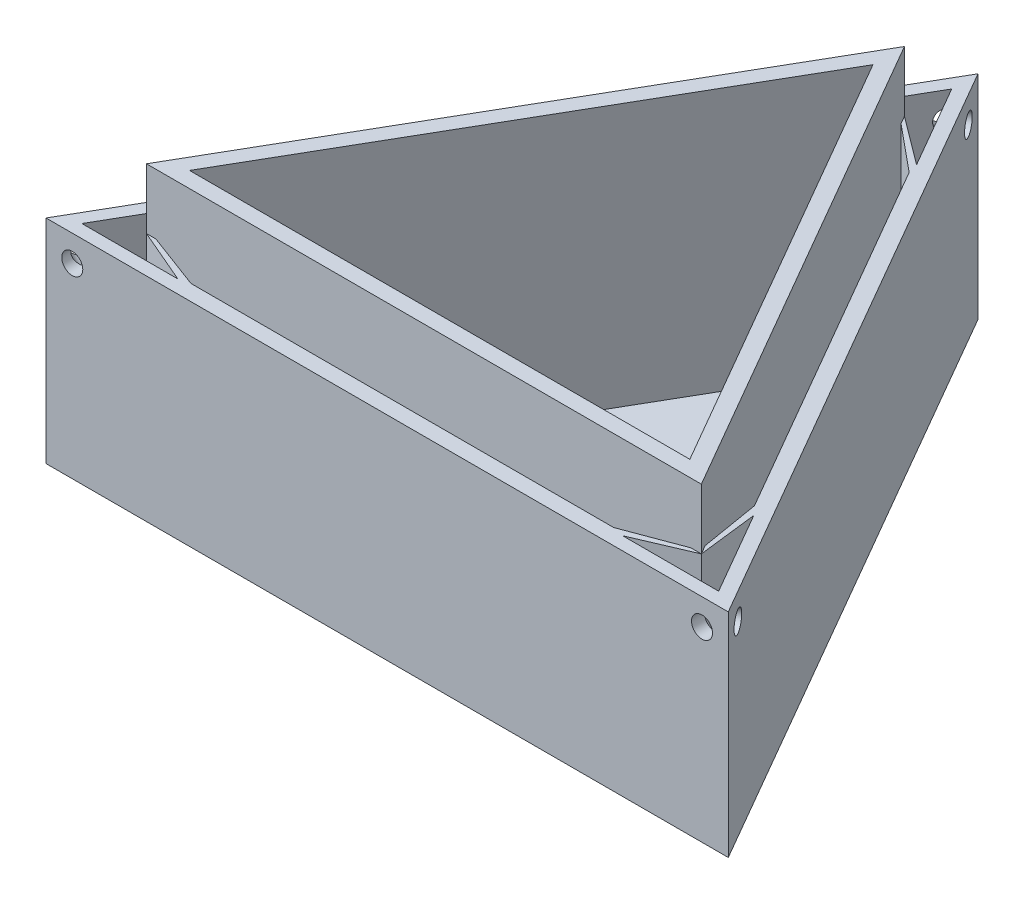
SolidWorks part; units mm, degrees
ref_plane "Front Plane" through (0, 0, 0) normal (0, 0, 1) x (1, 0, 0)
ref_plane "Top Plane" through (0, 0, 0) normal (0, 1, 0) x (1, 0, 0)
ref_plane "Right Plane" through (0, 0, 0) normal (1, 0, 0) x (0, 0, -1)
ref_plane "Plane1" through (0, -0.5, 0) normal (0, -1, 0) x (1, 0, 0)
sketch "Sketch1" plane through (0, -0.5, 0) normal (0, -1, 0) x (1, 0, 0)
  line L0 (64.9519, 37.5) -> (-64.9519, 37.5)
  line L1 (-64.9519, 37.5) -> (0, -75)
  line L2 (0, -75) -> (64.9519, 37.5)
extrude "Boss-Extrude1" add sketch "Sketch1" against normal blind 40.5
sketch "Sketch4" plane through (0, 40, 0) normal (0, 1, 0) x (-1, 0, 0)
  line L0 (0, -61) -> (-52.8275, 30.5)
  line L1 (-52.8275, 30.5) -> (52.8275, 30.5)
  line L2 (52.8275, 30.5) -> (0, -61)
extrude "Boss-Extrude2" add sketch "Sketch4" along normal blind 11.5
sketch "Sketch2" plane through (0, 40, 0) normal (0, 1, 0) x (-1, 0, 0)
  line L0 (-0.8996, -59.4418) -> (-51.8275, 28.7679)
  line L1 (-52.8275, 30.5) -> (0, -61) construction
  line L2 (0, -75) -> (-64.9519, 37.5) construction
  line L3 (-49.9476, 17.5119) -> (-9.7078, -52.1857)
  spline S0 degree 1 poles (-49.9476, 17.5119) (-51.8275, 28.7679) knots 0 0 1 1
  spline S2 degree 1 poles (-0.8996, -59.4418) (-9.7078, -52.1857) knots 0 0 1 1
  dimension "D1" = 3
extrude "Cut-Extrude1" cut sketch "Sketch2" against normal blind 38.5
sketch "Sketch3" plane through (0, 40, 0) normal (0, 1, 0) x (-1, 0, 0)
  line L0 (-50.8275, 30.5) -> (51.0283, 30.5)
  line L1 (52.8275, 30.5) -> (-52.8275, 30.5) construction
  line L3 (40.3402, 34.5) -> (-40.1395, 34.5)
  line L4 (-64.9519, 37.5) -> (64.9519, 37.5) construction
  spline S1 degree 1 poles (-50.8275, 30.5) (-40.1395, 34.5) knots 0 0 1 1
  spline S2 degree 1 poles (40.3402, 34.5) (51.0283, 30.5) knots 0 0 1 1
  dimension "D1" = 3
extrude "Cut-Extrude2" cut sketch "Sketch3" against normal blind 38.5
sketch "Sketch5" plane through (0, 40, 0) normal (0, 1, 0) x (-1, 0, 0)
  line L0 (50.048, 17.6857) -> (51.8275, 28.7679)
  line L1 (51.8275, 28.7679) -> (1, -59.2679)
  line L2 (1, -59.2679) -> (9.7078, -52.1857)
  line L3 (9.7078, -52.1857) -> (50.048, 17.6857)
  line L4 (64.9519, 37.5) -> (0, -75) construction
  line L5 (0, -61) -> (52.8275, 30.5) construction
  dimension "D1" = 3
extrude "Cut-Extrude3" cut sketch "Sketch5" against normal blind 38.5
sketch "Sketch6" plane through (0, 40, 0) normal (0, 1, 0) x (-1, 0, 0)
  spline S0 degree 1 poles (-42.3402, 35) (-60.6218, 35) knots 0 0 1 1
  spline S1 degree 1 poles (-51.481, 19.1677) (-60.6218, 35) knots 0 0 1 1
  spline S2 degree 1 poles (-52.8275, 30.5) (-51.481, 19.1677) knots 0 0 1 1
  spline S3 degree 1 poles (-42.3402, 35) (-52.8275, 30.5) knots 0 0 1 1
extrude "Cut-Extrude4" cut sketch "Sketch6" against normal blind 38.5
sketch "Sketch7" plane through (0, 40, 0) normal (0, 1, 0) x (-1, 0, 0)
  spline S0 degree 1 poles (60.6218, 35) (51.481, 19.1677) knots 0 0 1 1
  spline S1 degree 1 poles (60.6218, 35) (42.3402, 35) knots 0 0 1 1
  spline S2 degree 1 poles (52.8275, 30.5) (42.3402, 35) knots 0 0 1 1
  spline S3 degree 1 poles (51.481, 19.1677) (52.8275, 30.5) knots 0 0 1 1
extrude "Cut-Extrude5" cut sketch "Sketch7" against normal blind 38.5
sketch "Sketch8" plane through (0, 40, 0) normal (0, 1, 0) x (-1, 0, 0)
  spline S0 degree 1 poles (0, -70) (-9.1408, -54.1677) knots 0 0 1 1
  spline S1 degree 1 poles (9.1408, -54.1677) (0, -70) knots 0 0 1 1
  spline S2 degree 1 poles (0, -61) (9.1408, -54.1677) knots 0 0 1 1
  spline S3 degree 1 poles (-9.1408, -54.1677) (0, -61) knots 0 0 1 1
extrude "Cut-Extrude6" cut sketch "Sketch8" against normal blind 38.5
sketch "Sketch9" plane through (0, 51.5, 0) normal (0, 1, 0) x (-1, 0, 0)
  line L0 (47.6314, 27.5) -> (-47.6314, 27.5)
  line L1 (-47.6314, 27.5) -> (0, -55)
  line L2 (0, -55) -> (47.6314, 27.5)
  line L3 (52.8275, 30.5) -> (-52.8275, 30.5) construction
  line L4 (0, -61) -> (52.8275, 30.5) construction
  line L6 (-52.8275, 30.5) -> (0, -61) construction
  dimension "D1" = 3
  dimension "D2" = 3
  dimension "D3" = 3
extrude "Cut-Extrude7" cut sketch "Sketch9" against normal blind 50
hole_wizard "Ø18.0 (18) Diameter Hole1" positions "Sketch11" profile "Sketch10" hole size "Ø18.0" standard "ANSI Metric"
sketch "Sketch11" plane through (0, -0.5, 0) normal (0, -1, 0) x (-1, 0, 0)
  point P0 (0, 0)
sketch "Sketch10" plane through (0, -0.5, 0) normal (1, 0, 0) x (0, 0, -1)
  line L0 (0, 0) -> (0, 52)
  line L1 (0, 52) -> (9, 52)
  line L2 (9, 52) -> (9, 0)
  line L5 (9, 0) -> (0, 0)
  line L11 (0, -6.35) -> (0, 107.95) construction
  dimension "Thru Hole Dia." = 18
  dimension "Thru Hole Depth" = 52
hole_wizard "Ø2.45 (2.45) Diameter Hole1" positions "Sketch13" profile "Sketch12" hole size "Ø2.45" standard "ANSI Metric"
sketch "Sketch13" plane through (0, 1.5, 0) normal (0, 1, 0) x (1, 0, 0)
  point P0 (13.95, 13.95)
  point P1 (-13.95, -13.95)
  point P2 (13.95, -13.95)
  point P3 (-13.95, 13.95)
sketch "Sketch12" plane through (13.95, 1.5, -13.95) normal (1, 0, 0) x (0, 0, 1)
  line L0 (0, 0) -> (0, 2)
  line L1 (0, 2) -> (1.225, 2)
  line L2 (1.225, 2) -> (1.225, 0)
  line L5 (1.225, 0) -> (0, 0)
  line L11 (0, -6.35) -> (0, 107.95) construction
  dimension "Thru Hole Dia." = 2.45
  dimension "Thru Hole Depth" = 2
hole_wizard "Ø4.0 (4) Diameter Hole1" positions "Sketch15" profile "Sketch14" hole size "Ø4.0" standard "ANSI Metric"
sketch "Sketch15" plane through (0, 0, 37.5) normal (0, 0, 1) x (1, 0, 0)
  point P0 (59.9519, 35)
  point P1 (-59.9519, 35)
sketch "Sketch14" plane through (59.9519, 35, 37.5) normal (1, 0, 0) x (0, -1, 0)
  line L0 (0, 0) -> (0, 3)
  line L1 (0, 3) -> (2, 3)
  line L2 (2, 3) -> (2, 0)
  line L5 (2, 0) -> (0, 0)
  line L10 (0, 3) -> (-2, 3) construction
  line L11 (0, -6.35) -> (0, 107.95) construction
  dimension "Hole Dia." = 4
  dimension "Hole Depth" = 3
  dimension "Drill Angle" = 180
hole_wizard "Ø4.0 (4) Diameter Hole2" positions "Sketch17" profile "Sketch16" hole size "Ø4.0" standard "ANSI Metric"
sketch "Sketch17" plane through (-32.476, 0, -18.75) normal (-0.866, 0, -0.5) x (-0.5, 0, 0.866)
  point P0 (-59.9519, 35)
  point P1 (59.9519, 35)
sketch "Sketch16" plane through (-2.5, 35, -70.6699) normal (0, 1, 0) x (-0.5, 0, 0.866)
  line L0 (0, 0) -> (0, 3)
  line L1 (0, 3) -> (2, 3)
  line L2 (2, 3) -> (2, 0)
  line L5 (2, 0) -> (0, 0)
  line L10 (0, 3) -> (-2, 3) construction
  line L11 (0, -6.35) -> (0, 107.95) construction
  dimension "Hole Dia." = 4
  dimension "Hole Depth" = 3
  dimension "Drill Angle" = 180
hole_wizard "Ø4.0 (4) Diameter Hole3" positions "Sketch19" profile "Sketch18" hole size "Ø4.0" standard "ANSI Metric"
sketch "Sketch19" plane through (32.476, 0, -18.75) normal (0.866, 0, -0.5) x (-0.5, 0, -0.866)
  point P0 (59.9519, 35)
  point P1 (-59.9519, 35)
sketch "Sketch18" plane through (2.5, 35, -70.6699) normal (0, 1, 0) x (-0.5, 0, -0.866)
  line L0 (0, 0) -> (0, 3)
  line L1 (0, 3) -> (2, 3)
  line L2 (2, 3) -> (2, 0)
  line L5 (2, 0) -> (0, 0)
  line L10 (0, 3) -> (-2, 3) construction
  line L11 (0, -6.35) -> (0, 107.95) construction
  dimension "Hole Dia." = 4
  dimension "Hole Depth" = 3
  dimension "Drill Angle" = 180
